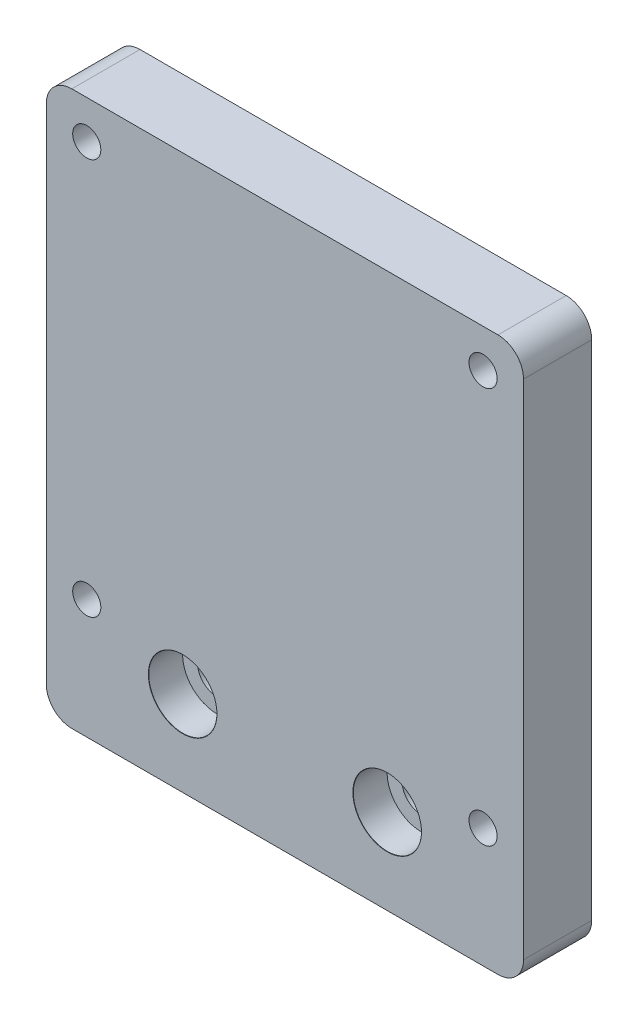
SolidWorks part; units mm, degrees
ref_plane "Front" through (0, 0, 0) normal (0, 0, 1) x (1, 0, 0)
ref_plane "Top" through (0, 0, 0) normal (0, 1, 0) x (1, 0, 0)
ref_plane "Right" through (0, 0, 0) normal (1, 0, 0) x (0, 0, -1)
sketch "Sketch1" plane through (0, 0, 0) normal (0, 0, 1) x (1, 0, 0)
  line L0 (-12, -22.5) -> (12, -22.5) construction
  line L1 (-28, -32.5) -> (28, -32.5)
  line L2 (-28, -32.5) -> (-28, 32.5)
  line L3 (-28, 32.5) -> (28, 32.5)
  line L4 (28, -32.5) -> (28, 32.5)
  line L5 (-28, -32.5) -> (28, 32.5) construction
  line L6 (-28, 32.5) -> (28, -32.5) construction
  line L7 (0, 0) -> (0, -22.5) construction
  line L8 (-23.25, 28) -> (23.25, -18.5) construction
  line L9 (-23.25, 28) -> (23.25, 28) construction
  line L10 (-23.25, 28) -> (-23.25, -18.5) construction
  line L11 (-23.25, -18.5) -> (23.25, -18.5) construction
  line L12 (23.25, 28) -> (23.25, -18.5) construction
  line L13 (23.25, 28) -> (-23.25, -18.5) construction
  line L14 (0, 4.75) -> (0, 0) construction
  point P0 (0, 0)
  point P15 (0, 6.3087)
  dimension "D1" = 56
  dimension "D2" = 65
  dimension "D3" = 24
  dimension "D4" = 10
  dimension "D5" = 46.5
  dimension "D6" = 46.5
  dimension "D7" = 4.5
  dimension "D8" = 37.25
extrude "Boss-Extrude1" add sketch "Sketch1" along normal blind 8
fillet "Fillet1" radius 3 4 edges at (28, -32.5, 4) (-28, -32.5, 4) (-28, 32.5, 4) (28, 32.5, 4)
hole_wizard "CBORE for M4 SHCS1" positions "Sketch2" profile "Sketch3" counterbore size "M4" standard "ANSI Metric" end condition through all
sketch "Sketch2" plane through (0, 0, 8) normal (0, 0, 1) x (1, 0, 0)
  point P0 (-12, -22.5)
  point P3 (12, -22.5)
sketch "Sketch3" plane through (-12, -22.5, 8) normal (1, 0, 0) x (0, -1, 0)
  line L0 (0, 0) -> (0, 8)
  line L1 (0, 8) -> (2.25, 8)
  line L3 (2.25, 8) -> (2.25, 4)
  line L4 (4, 4) -> (2.25, 4)
  line L5 (4, 4) -> (4, 0.025)
  line L6 (4, 0.025) -> (4.025, 0)
  line L7 (4.025, 0) -> (0, 0)
  line L8 (-4, 0.025) -> (-4.025, 0) construction
  line L11 (0, -6.35) -> (0, 107.95) construction
  dimension "Thru Hole Dia." = 4.5
  dimension "Thru Hole Depth" = 8
  dimension "C'Bore Dia." = 8
  dimension "C'Bore Depth" = 4
  dimension "Near C'Sink Dia." = 8.05
  dimension "Near C'Sink Angle" = 90
hole_wizard "M4x0.7 Tapped Hole1" positions "Sketch5" profile "Sketch6" tap size "M4x0.7" standard "ANSI Metric"
sketch "Sketch5" plane through (0, 0, 8) normal (0, 0, 1) x (1, 0, 0)
  point P0 (-23.25, -18.5)
  point P3 (23.25, -18.5)
  point P6 (23.25, 28)
  point P9 (-23.25, 28)
sketch "Sketch6" plane through (-23.25, -18.5, 8) normal (1, 0, 0) x (0, -1, 0)
  line L0 (0, 0) -> (0, 11.0914)
  line L1 (0, 11.0914) -> (1.65, 10.1)
  line L2 (1.65, 10.1) -> (1.65, 0)
  line L5 (1.65, 0) -> (0, 0)
  line L10 (0, 11.0914) -> (-1.65, 10.1) construction
  line L11 (0, -6.35) -> (0, 107.95) construction
  dimension "Tap Drill Dia." = 3.3
  dimension "Tap Drill Depth" = 10.1
  dimension "Drill Angle" = 118
cosmetic thread "Hole Thread1"
cosmetic thread "Hole Thread2"
cosmetic thread "Hole Thread3"
cosmetic thread "Hole Thread4"
